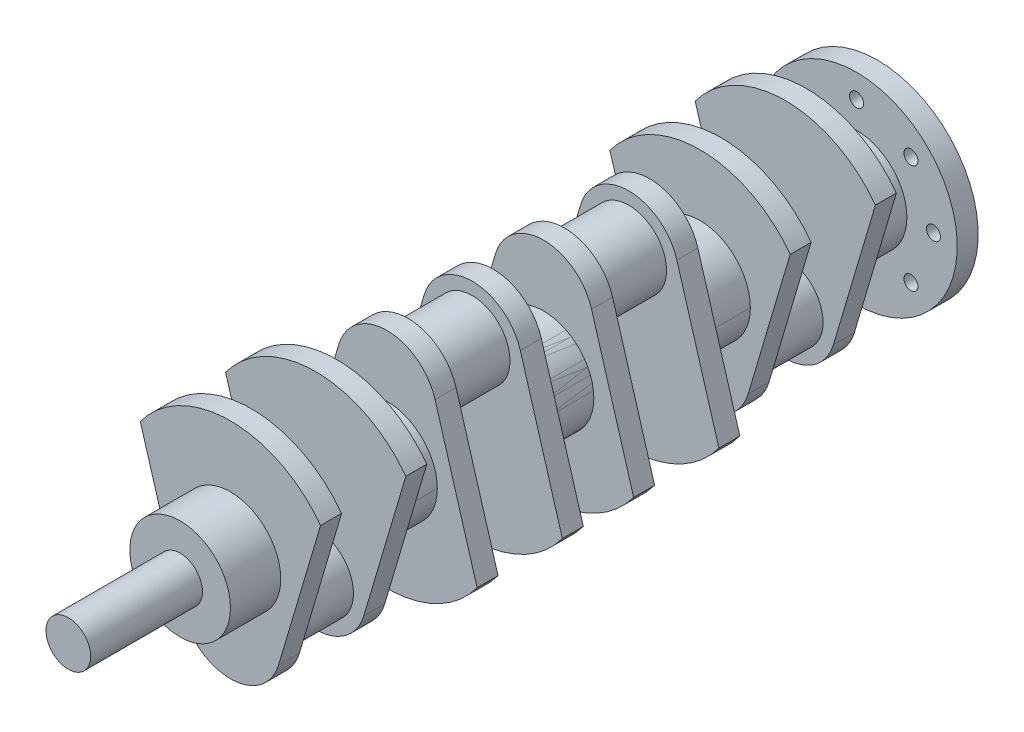
SolidWorks part; units mm, degrees
ref_plane "Front Plane" through (0, 0, 0) normal (0, 0, 1) x (1, 0, 0)
ref_plane "Top Plane" through (0, 0, 0) normal (0, 1, 0) x (1, 0, 0)
ref_plane "Right Plane" through (0, 0, 0) normal (1, 0, 0) x (0, 0, -1)
sketch "Sketch1" plane through (0, 0, 0) normal (0, 0, 1) x (1, 0, 0)
  line L0 (0, 67.2754) -> (0, -44) construction
  line L1 (-141.8189, 0) -> (134.7372, 0) construction
  line L2 (-64.4847, 47.3469) -> (-34.4075, -54.192)
  line L3 (64.4847, 47.3469) -> (34.4075, -54.192)
  circle A0 centre (0, -44) radius 35.8853
  arc A1 (-64.4847, 47.3469) -> (64.4847, 47.3469) centre (0, 0) cw
  point P9 (0, 0)
  point P12 (0, 0)
  dimension "D1" = 33
  dimension "D2" = 44
extrude "Boss-Extrude1" add sketch "Sketch1" along normal blind 15 contours A1 L2 A0 L3 | A0
sketch "Sketch4" plane through (0, 0, 0) normal (0, 0, -1) x (-1, 0, 0)
  circle A0 centre (0, -44) radius 27
extrude "Boss-Extrude2" add sketch "Sketch4" along normal blind 46 contours A0
ref_plane "Plane1" through (0, 0, -23) normal (0, 0, -1) x (-1, 0, 0)
mirror "Mirror1" about plane through (0, 0, -23) normal (0, 0, -1) of "Boss-Extrude1"
sketch "Sketch6" plane through (0, 0, 15) normal (0, 0, 1) x (1, 0, 0)
  circle A0 centre (0, 0) radius 36
extrude "Boss-Extrude3" add sketch "Sketch6" along normal blind 36
mirror "Mirror2" about plane through (0, 0, -23) normal (0, 0, -1) of "Boss-Extrude3"
ref_plane "Plane2" through (0, 0, -79) normal (0, 0, -1) x (-1, 0, 0)
ref_plane "Plane9" through (0, 0, -79) normal (0, 0, -1) x (-1, 0, 0)
mirror "Mirror13" about plane through (0, 0, -79) normal (0, 0, -1) of bodies 106
move or copy body "Body-Move/Copy2" bodies to move or copy 121 copy no rotation origin (0, 0.0574, -135) rotation axis (1, 0, 0) rotation angle 180
ref_plane "Plane11" through (0, 0, -191) normal (0, 0, -1) x (-1, 0, 0)
mirror "Mirror15" about plane through (0, 0, -191) normal (0, 0, -1) of bodies 106 122
sketch "Sketch8" plane through (0, 0, 51) normal (0, 0, 1) x (1, 0, 0)
  circle A0 centre (0, 0) radius 16
extrude "Boss-Extrude5" add sketch "Sketch8" along normal blind 80
sketch "Sketch9" plane through (0, 0, -433) normal (0, 0, -1) x (-1, 0, 0)
  circle A0 centre (0, 0) radius 72
extrude "Boss-Extrude6" add sketch "Sketch9" along normal blind 15
sketch "Sketch10" plane through (0, 0, -448) normal (0, 0, -1) x (-1, 0, 0)
  line L0 (0, 87.7576) -> (0, -92.4092) construction
  line L1 (-101.9992, 0) -> (165.6296, 0) construction
  circle A0 centre (0, 0) radius 55 construction
  circle A1 centre (0, 55) radius 5
  circle A2 centre (38.8909, 38.8909) radius 5
  circle A3 centre (55, 0) radius 5
  circle A4 centre (38.8909, -38.8909) radius 5
  circle A5 centre (0, -55) radius 5
  circle A6 centre (-38.8909, -38.8909) radius 5
  circle A7 centre (-55, 0) radius 5
  circle A8 centre (-38.8909, 38.8909) radius 5
  point P25 (0, 0)
  dimension "D1" = 8
extrude "Cut-Extrude2" cut sketch "Sketch10" against normal blind 15
